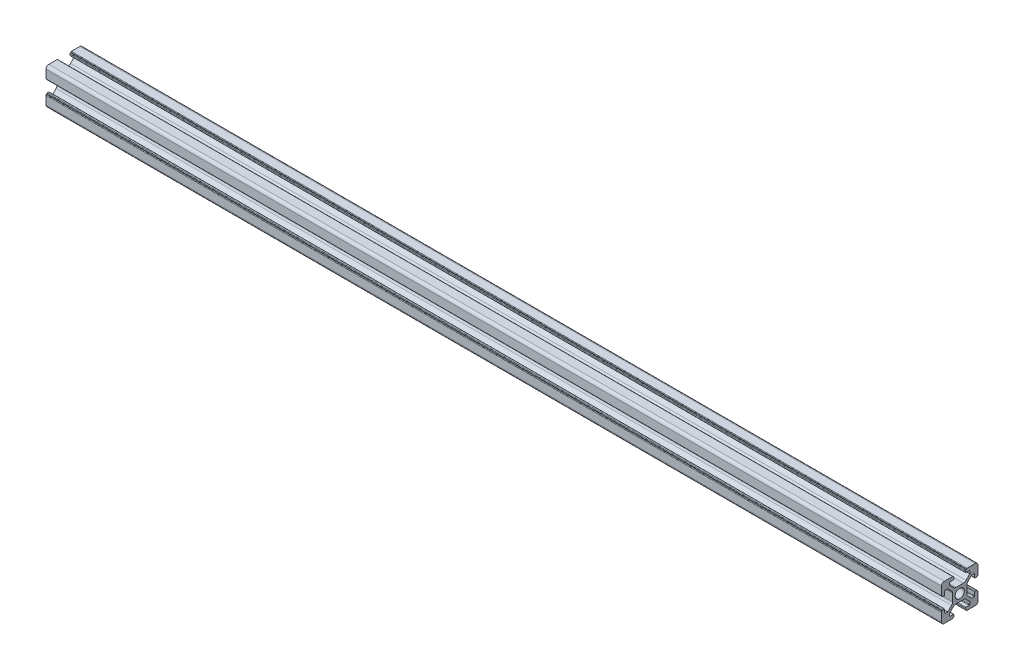
SolidWorks part; units mm, degrees
ref_plane "前视基准面" through (0, 0, 0) normal (0, 0, 1) x (1, 0, 0)
ref_plane "上视基准面" through (0, 0, 0) normal (0, 1, 0) x (1, 0, 0)
ref_plane "右视基准面" through (0, 0, 0) normal (1, 0, 0) x (0, 0, -1)
sketch "草图1" plane through (0, 0, 0) normal (0, 0, 1) x (1, 0, 0)
  line L0 (-48.2957, 66.9097) -> (441.7043, 66.9097)
  dimension "D1" = 490
other "铝型材 2020(1)"
ref_plane "基准面4" through (-48.2957, 66.9097, 0) normal (1, 0, 0) x (0, 1, 0)
sketch "草图11" plane through (-48.2957, 66.9097, 0) normal (1, 0, 0) x (0, 1, 0)
  line L0 (3.9, 0) -> (3.9, -2.0109)
  line L1 (4.4858, -3.4251) -> (6.5607, -5.5)
  line L2 (6.5607, -5.5) -> (7.9, -5.5)
  line L3 (8.2, -5.2) -> (8.2, -3.4)
  line L4 (8.5, -3.1) -> (9.2, -3.1)
  line L5 (9.5, -3.4) -> (9.5, -3.6)
  line L6 (9.5, -3.6) -> (9.7, -3.6)
  line L7 (10, -3.9) -> (10, -8.5)
  line L8 (8.5, -10) -> (3.9, -10)
  line L9 (3.1, -9.2) -> (3.1, -8.5)
  line L10 (3.4, -8.2) -> (5.2, -8.2)
  line L11 (5.5, -7.9) -> (5.5, -6.6849)
  line L12 (5.4121, -6.4728) -> (3.4251, -4.4858)
  line L13 (2.0109, -3.9) -> (0, -3.9)
  line L14 (0, -3.9) -> (-2.0109, -3.9)
  line L15 (-3.4251, -4.4858) -> (-5.4121, -6.4728)
  line L16 (-5.5, -6.6849) -> (-5.5, -7.9)
  line L17 (-5.2, -8.2) -> (-3.4, -8.2)
  line L18 (-3.1, -8.5) -> (-3.1, -9.2)
  line L19 (-3.9, -10) -> (-8.5, -10)
  line L20 (-10, -8.5) -> (-10, -3.9)
  line L21 (-9.7, -3.6) -> (-9.5, -3.6)
  line L22 (-9.5, -3.6) -> (-9.5, -3.4)
  line L23 (-9.2, -3.1) -> (-8.5, -3.1)
  line L24 (-8.2, -3.4) -> (-8.2, -5.2)
  line L25 (-7.9, -5.5) -> (-6.6849, -5.5)
  line L26 (-6.4728, -5.4121) -> (-4.4858, -3.4251)
  line L27 (-3.9, -2.0109) -> (-3.9, 0)
  line L28 (-3.9, 0) -> (-3.9, 2.0109)
  line L29 (-4.4858, 3.4251) -> (-6.4728, 5.4121)
  line L30 (-6.6849, 5.5) -> (-7.9, 5.5)
  line L31 (-8.2, 5.2) -> (-8.2, 3.4)
  line L32 (-8.5, 3.1) -> (-9.2, 3.1)
  line L33 (-9.5, 3.4) -> (-9.5, 3.6)
  line L34 (-9.5, 3.6) -> (-9.7, 3.6)
  line L35 (-10, 3.9) -> (-10, 8.5)
  line L36 (-8.5, 10) -> (-3.9, 10)
  line L37 (-3.6, 9.7) -> (-3.6, 9.5)
  line L38 (-3.6, 9.5) -> (-3.4, 9.5)
  line L39 (-3.1, 9.2) -> (-3.1, 8.5)
  line L40 (-3.4, 8.2) -> (-5.2, 8.2)
  line L41 (-5.5, 7.9) -> (-5.5, 6.6849)
  line L42 (-5.4121, 6.4728) -> (-3.4251, 4.4858)
  line L43 (-2.0109, 3.9) -> (0, 3.9)
  line L44 (0, 3.9) -> (2.0109, 3.9)
  line L45 (3.4251, 4.4858) -> (5.4121, 6.4728)
  line L46 (5.5, 6.6849) -> (5.5, 7.9)
  line L47 (5.2, 8.2) -> (3.4, 8.2)
  line L48 (3.1, 8.5) -> (3.1, 9.2)
  line L49 (3.4, 9.5) -> (3.6, 9.5)
  line L50 (3.6, 9.5) -> (3.6, 9.7)
  line L51 (3.9, 10) -> (8.5, 10)
  line L52 (10, 8.5) -> (10, 3.9)
  line L53 (9.7, 3.6) -> (9.5, 3.6)
  line L54 (9.5, 3.6) -> (9.5, 3.4)
  line L55 (9.2, 3.1) -> (8.5, 3.1)
  line L56 (8.2, 3.4) -> (8.2, 5.2)
  line L57 (7.9, 5.5) -> (6.6849, 5.5)
  line L58 (6.4728, 5.4121) -> (4.4858, 3.4251)
  line L59 (3.9, 2.0109) -> (3.9, 0)
  circle A0 centre (0, 0) radius 2.5
  arc A1 (3.9, -2.0109) -> (4.4858, -3.4251) centre (5.9, -2.0109) ccw
  arc A2 (7.9, -5.5) -> (8.2, -5.2) centre (7.9, -5.2) ccw
  arc A3 (8.5, -3.1) -> (8.2, -3.4) centre (8.5, -3.4) ccw
  arc A4 (9.5, -3.4) -> (9.2, -3.1) centre (9.2, -3.4) ccw
  arc A5 (10, -3.9) -> (9.7, -3.6) centre (9.7, -3.9) ccw
  arc A6 (8.5, -10) -> (10, -8.5) centre (8.5, -8.5) ccw
  arc A7 (3.6, -9.7) -> (3.9, -10) centre (3.9, -9.7) ccw
  arc A8 (3.6, -9.7) -> (3.4, -9.5) centre (3.4, -9.7) ccw
  arc A9 (3.1, -9.2) -> (3.4, -9.5) centre (3.4, -9.2) ccw
  arc A10 (3.4, -8.2) -> (3.1, -8.5) centre (3.4, -8.5) ccw
  arc A11 (5.2, -8.2) -> (5.5, -7.9) centre (5.2, -7.9) ccw
  arc A12 (5.5, -6.6849) -> (5.4121, -6.4728) centre (5.2, -6.6849) ccw
  arc A13 (3.4251, -4.4858) -> (2.0109, -3.9) centre (2.0109, -5.9) ccw
  arc A14 (-2.0109, -3.9) -> (-3.4251, -4.4858) centre (-2.0109, -5.9) ccw
  arc A15 (-5.4121, -6.4728) -> (-5.5, -6.6849) centre (-5.2, -6.6849) ccw
  arc A16 (-5.5, -7.9) -> (-5.2, -8.2) centre (-5.2, -7.9) ccw
  arc A17 (-3.1, -8.5) -> (-3.4, -8.2) centre (-3.4, -8.5) ccw
  arc A18 (-3.4, -9.5) -> (-3.1, -9.2) centre (-3.4, -9.2) ccw
  arc A19 (-3.4, -9.5) -> (-3.6, -9.7) centre (-3.4, -9.7) ccw
  arc A20 (-3.9, -10) -> (-3.6, -9.7) centre (-3.9, -9.7) ccw
  arc A21 (-10, -8.5) -> (-8.5, -10) centre (-8.5, -8.5) ccw
  arc A22 (-9.7, -3.6) -> (-10, -3.9) centre (-9.7, -3.9) ccw
  arc A23 (-9.2, -3.1) -> (-9.5, -3.4) centre (-9.2, -3.4) ccw
  arc A24 (-8.2, -3.4) -> (-8.5, -3.1) centre (-8.5, -3.4) ccw
  arc A25 (-8.2, -5.2) -> (-7.9, -5.5) centre (-7.9, -5.2) ccw
  arc A26 (-6.6849, -5.5) -> (-6.4728, -5.4121) centre (-6.6849, -5.2) ccw
  arc A27 (-4.4858, -3.4251) -> (-3.9, -2.0109) centre (-5.9, -2.0109) ccw
  arc A28 (-3.9, 2.0109) -> (-4.4858, 3.4251) centre (-5.9, 2.0109) ccw
  arc A29 (-6.4728, 5.4121) -> (-6.6849, 5.5) centre (-6.6849, 5.2) ccw
  arc A30 (-7.9, 5.5) -> (-8.2, 5.2) centre (-7.9, 5.2) ccw
  arc A31 (-8.5, 3.1) -> (-8.2, 3.4) centre (-8.5, 3.4) ccw
  arc A32 (-9.5, 3.4) -> (-9.2, 3.1) centre (-9.2, 3.4) ccw
  arc A33 (-10, 3.9) -> (-9.7, 3.6) centre (-9.7, 3.9) ccw
  arc A34 (-8.5, 10) -> (-10, 8.5) centre (-8.5, 8.5) ccw
  arc A35 (-3.6, 9.7) -> (-3.9, 10) centre (-3.9, 9.7) ccw
  arc A36 (-3.1, 9.2) -> (-3.4, 9.5) centre (-3.4, 9.2) ccw
  arc A37 (-3.4, 8.2) -> (-3.1, 8.5) centre (-3.4, 8.5) ccw
  arc A38 (-5.2, 8.2) -> (-5.5, 7.9) centre (-5.2, 7.9) ccw
  arc A39 (-5.5, 6.6849) -> (-5.4121, 6.4728) centre (-5.2, 6.6849) ccw
  arc A40 (-3.4251, 4.4858) -> (-2.0109, 3.9) centre (-2.0109, 5.9) ccw
  arc A41 (2.0109, 3.9) -> (3.4251, 4.4858) centre (2.0109, 5.9) ccw
  arc A42 (5.4121, 6.4728) -> (5.5, 6.6849) centre (5.2, 6.6849) ccw
  arc A43 (5.5, 7.9) -> (5.2, 8.2) centre (5.2, 7.9) ccw
  arc A44 (3.1, 8.5) -> (3.4, 8.2) centre (3.4, 8.5) ccw
  arc A45 (3.4, 9.5) -> (3.1, 9.2) centre (3.4, 9.2) ccw
  arc A46 (3.9, 10) -> (3.6, 9.7) centre (3.9, 9.7) ccw
  arc A47 (10, 8.5) -> (8.5, 10) centre (8.5, 8.5) ccw
  arc A48 (9.7, 3.6) -> (10, 3.9) centre (9.7, 3.9) ccw
  arc A49 (9.2, 3.1) -> (9.5, 3.4) centre (9.2, 3.4) ccw
  arc A50 (8.2, 3.4) -> (8.5, 3.1) centre (8.5, 3.4) ccw
  arc A51 (8.2, 5.2) -> (7.9, 5.5) centre (7.9, 5.2) ccw
  arc A52 (6.6849, 5.5) -> (6.4728, 5.4121) centre (6.6849, 5.2) ccw
  arc A53 (4.4858, 3.4251) -> (3.9, 2.0109) centre (5.9, 2.0109) ccw
  point P0 (0, 0)
